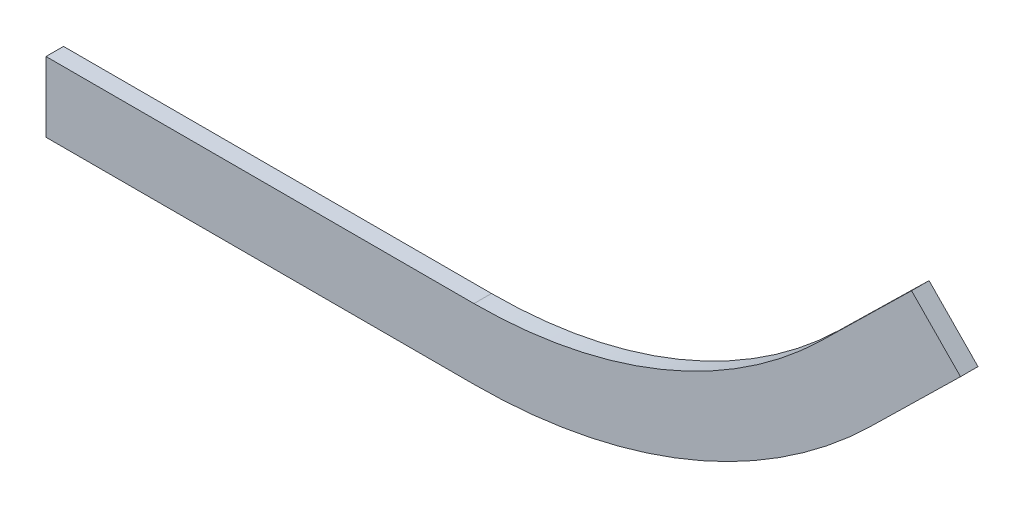
SolidWorks part; units mm, degrees
other "Папка сварных швов"
ref_plane "Front" through (0, 0, 0) normal (0, 0, 1) x (1, 0, 0)
ref_plane "Top" through (0, 0, 0) normal (0, 1, 0) x (1, 0, 0)
ref_plane "Right" through (0, 0, 0) normal (1, 0, 0) x (0, 0, -1)
sketch "Sketch4" plane through (0, 0, 0) normal (0, 0, 1) x (1, 0, 0)
  line B0 (50, 40) -> (244.6554, 40)
  line B1 (443.3207, 121.0515) -> (459.0665, 136.465)
  line B2 (471.3054, 92.4708) -> (487.0475, 107.8807)
  line B3 (50, 0) -> (244.6502, 0)
  line B4 (0, 40) -> (50, 40)
  line B5 (459.0665, 136.465) -> (494.7969, 171.4413)
  line B6 (0, 0) -> (50, 0)
  line B7 (487.0475, 107.8807) -> (522.7779, 142.857)
  line B8 (494.7969, 171.4413) -> (522.7779, 142.857)
  line B9 (0, 40) -> (0, 0)
  arc B10 (244.6502, 0) -> (471.3054, 92.4708) centre (244.6502, 324.0128) ccw
  arc B11 (244.6554, 40) -> (443.3207, 121.0515) centre (244.6554, 324) ccw
  line B12 (0, 0) -> (522.7779, 0) construction
sketch_block_instance "дуга малирования-1"
sketch_block "Block2" parameters "D1"=522.7779
extrude "Boss-Extrude1" add sketch "Sketch4" against normal mid plane 10
